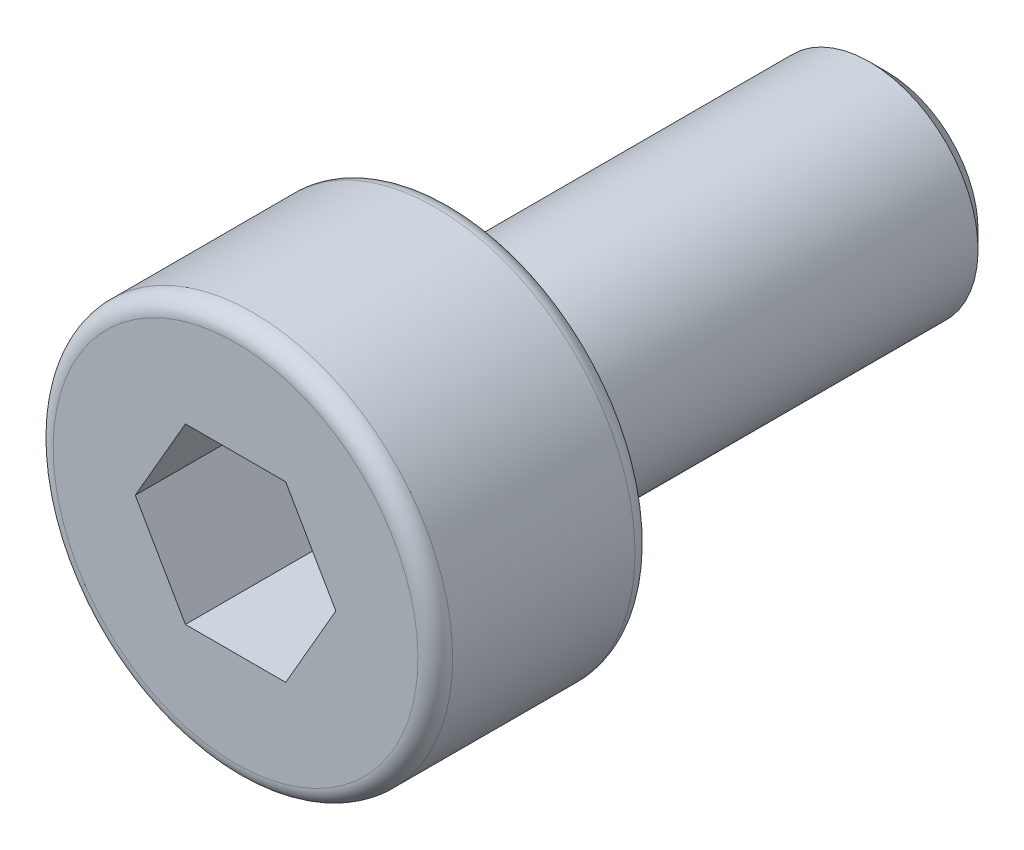
SolidWorks part; units mm, degrees
ref_plane "前视基准面" through (0, 0, 0) normal (0, 0, 1) x (1, 0, 0)
ref_plane "上视基准面" through (0, 0, 0) normal (0, 1, 0) x (1, 0, 0)
ref_plane "右视基准面" through (0, 0, 0) normal (1, 0, 0) x (0, 0, -1)
sketch "草图2" plane through (0, 0, 0) normal (1, 0, 0) x (0, 0, -1)
  line L0 (0, 0) -> (0, 2.3)
  line L1 (0, 2.3) -> (2.5, 2.3)
  line L2 (2.5, 2.3) -> (2.5, 1.25)
  line L3 (2.5, 1.25) -> (7.5, 1.25)
  line L5 (7.5, 1.25) -> (7.5, 0)
  line L6 (7.5, 0) -> (0, 0)
  dimension "D1" = 1.25
  dimension "D2" = 2.3
  dimension "D3" = 2.5
  dimension "D4" = 5
revolve "旋转1" add sketch "草图2" angle 360 about L6
fillet "圆角1" radius 0.2 2 edges at (0, 2.3, -2.5) (0, 2.3, 0)
chamfer "倒角1" distance 0.2 angle 45 1 edges at (0, 1.25, -7.5)
sketch "草图3" plane through (0, 0, 0) normal (0, 0, 1) x (1, 0, 0)
  line L1 (1.1547, 0) -> (0.5774, 1)
  line L2 (0.5774, 1) -> (-0.5774, 1)
  line L3 (-0.5774, 1) -> (-1.1547, 0)
  line L4 (-1.1547, 0) -> (-0.5774, -1)
  line L5 (-0.5774, -1) -> (0.5774, -1)
  line L6 (0.5774, -1) -> (1.1547, 0)
  circle A0 centre (0, 0) radius 1 construction
  dimension "D1" = 2
extrude "切除-拉伸1" cut sketch "草图3" against normal blind 1.5
